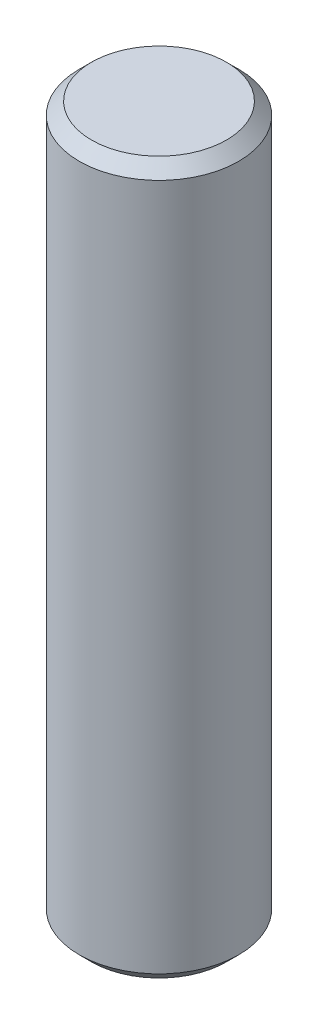
SolidWorks part; units mm, degrees
ref_plane "Front" through (0, 0, 0) normal (0, 0, 1) x (1, 0, 0)
ref_plane "Top" through (0, 0, 0) normal (0, 1, 0) x (1, 0, 0)
ref_plane "Right" through (0, 0, 0) normal (1, 0, 0) x (0, 0, -1)
sketch "Sketch1" plane through (0, 0, 0) normal (0, 1, 0) x (1, 0, 0)
  circle A0 centre (0, 0) radius 1.651
  dimension "D1" = 3.302
extrude "Boss-Extrude1" add sketch "Sketch1" along normal blind 14.732
chamfer "Chamfer1" distance 0.254 angle 45 2 edges at (0, 14.732, 1.651) (0, 0, 1.651)
